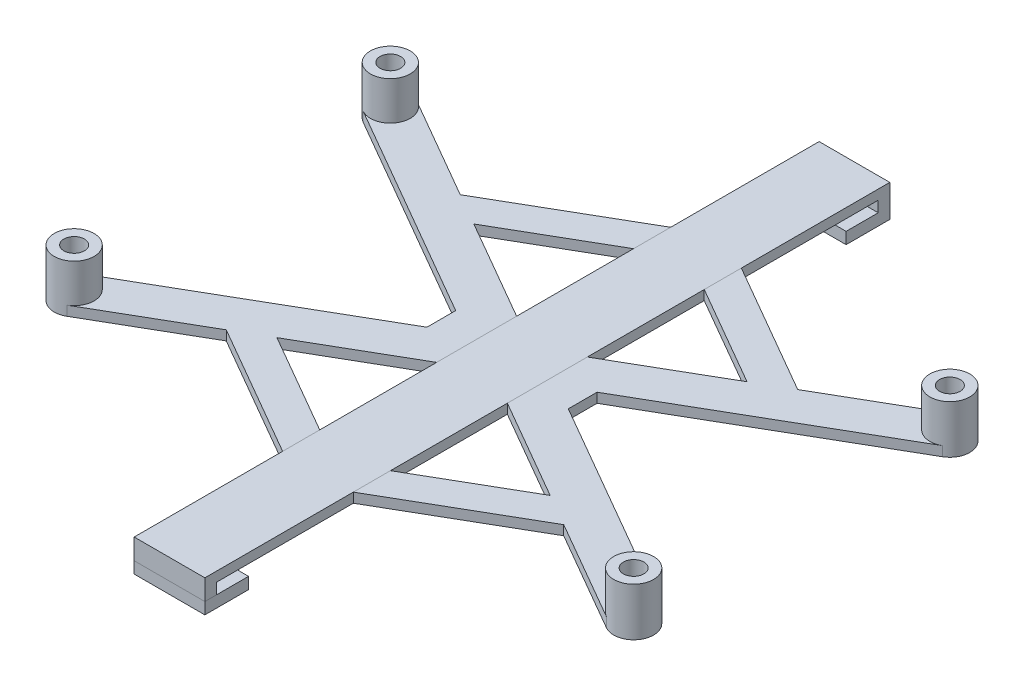
SolidWorks part; units mm, degrees
ref_plane "前视基准面" through (0, 0, 0) normal (0, 0, 1) x (1, 0, 0)
ref_plane "上视基准面" through (0, 0, 0) normal (0, 1, 0) x (1, 0, 0)
ref_plane "右视基准面" through (0, 0, 0) normal (1, 0, 0) x (0, 0, -1)
other "Configuration Table"
sketch "草图1" plane through (0, 0, 0) normal (0, 1, 0) x (1, 0, 0)
  line L0 (-15.0927, 0) -> (15.0927, 0) construction
  line L1 (0, -51.5) -> (0, 51.5) construction
  line L2 (-5.5, 51.5) -> (5.5, 51.5) construction
  line L3 (-5.5, -51.5) -> (5.5, -51.5) construction
  line L4 (-5.5, 51.5) -> (-5.5, 46.5)
  line L5 (-5.5, 46.5) -> (5.5, 46.5)
  line L6 (5.5, 46.5) -> (5.5, 51.5)
  line L7 (-5.5, 51.5) -> (-5.5, 53.3)
  line L8 (-5.5, 53.3) -> (5.5, 53.3)
  line L9 (5.5, 53.3) -> (5.5, 51.5)
  line L10 (-5.5, -51.5) -> (5.5, -51.5) construction
  line L11 (5.5, -53.3) -> (5.5, -51.5)
  line L12 (-5.5, -53.3) -> (5.5, -53.3)
  line L13 (-5.5, -51.5) -> (-5.5, -53.3)
  line L14 (5.5, -46.5) -> (5.5, -51.5)
  line L15 (-5.5, -46.5) -> (5.5, -46.5)
  line L16 (-5.5, -51.5) -> (-5.5, -46.5)
  point P4 (0, 0)
  point P8 (0, 0)
  point P10 (0, 51.5)
  point P21 (0, -51.5)
  dimension "D1" = 11
  dimension "D2" = 103
  dimension "D3" = 5
  dimension "D4" = 1.8
extrude "凸台-拉伸1" add sketch "草图1" against normal blind 1.8 contours L9 L8 L7 L4 L5 L6 | L16 L13 L12 L11 L14 L15
sketch "草图2" plane through (0, 0, 0) normal (0, 1, 0) x (1, 0, 0)
  line L0 (-5.5, 51.5) -> (5.5, 51.5) construction
  line L1 (-5.5, 51.5) -> (5.5, 51.5)
  line L2 (-52.579, 0) -> (52.579, 0) construction
  line L3 (-5.5, -51.5) -> (5.5, -51.5)
  line L4 (5.5, 46.5) -> (5.5, 53.3)
  line L5 (5.5, 53.3) -> (-5.5, 53.3)
  line L6 (-5.5, 53.3) -> (-5.5, 46.5)
  line L7 (-5.5, 46.5) -> (5.5, 46.5)
  line L8 (5.5, 51.5) -> (5.5, 53.3)
  line L9 (5.5, 53.3) -> (-5.5, 53.3)
  line L10 (-5.5, 53.3) -> (-5.5, 51.5)
  line L12 (-5.5, -53.3) -> (-5.5, -51.5)
  line L13 (5.5, -53.3) -> (-5.5, -53.3)
  line L14 (5.5, -51.5) -> (5.5, -53.3)
  point P9 (0, 0)
  dimension "D1" = 0
extrude "凸台-拉伸2" add sketch "草图2" along normal blind 1.7
sketch "草图3" plane through (0, 1.7, 0) normal (0, 1, 0) x (1, 0, 0)
  line L1 (-5.5, 53.3) -> (5.5, 53.3)
  line L2 (-5.5, 53.3) -> (-5.5, -53.3)
  line L3 (-5.5, -53.3) -> (5.5, -53.3)
  line L4 (5.5, 53.3) -> (5.5, -53.3)
extrude "凸台-拉伸3" add sketch "草图3" along normal blind 1.5
sketch "草图4" plane through (0, 3.2, 0) normal (0, 1, 0) x (1, 0, 0)
  line L0 (-100.345, 0) -> (100.345, 0) construction
  line L1 (0, -56.8016) -> (0, 56.8016) construction
  line L2 (-45.09, 21.9203) -> (-11, 2.2385)
  line L3 (-5.5, 53.3) -> (-5.5, -53.3) construction
  line L4 (-41.99, 27.2897) -> (-26.2617, 18.2089)
  line L5 (-5.5, 6.2222) -> (-5.5, -0.937)
  line L6 (41.99, 27.2897) -> (26.2617, 18.2089)
  line L7 (45.09, 21.9203) -> (11, 2.2385)
  line L8 (-5.5, -6.2222) -> (-5.5, 0.937)
  line L9 (45.09, -21.9203) -> (11, -2.2385)
  line L10 (41.99, -27.2897) -> (26.2617, -18.2089)
  line L11 (-45.09, -21.9203) -> (-11, -2.2385)
  line L12 (-41.99, -27.2897) -> (-26.2617, -18.2089)
  line L13 (-21.2617, 15.3222) -> (-5.5, 24.4222)
  line L14 (-26.2617, 18.2089) -> (-5.5, 30.1957)
  line L15 (-5.5, 30.1957) -> (-5.5, 24.4222)
  line L16 (5.5, 30.1957) -> (5.5, 24.4222)
  line L17 (-21.2617, 15.3222) -> (-5.5, 6.2222)
  line L18 (21.2617, 15.3222) -> (5.5, 24.4222)
  line L19 (26.2617, 18.2089) -> (5.5, 30.1957)
  line L20 (21.2617, -15.3222) -> (5.5, -24.4222)
  line L21 (5.5, -30.1957) -> (5.5, -24.4222)
  line L22 (26.2617, -18.2089) -> (5.5, -30.1957)
  line L23 (-21.2617, -15.3222) -> (-5.5, -24.4222)
  line L24 (-5.5, -30.1957) -> (-5.5, -24.4222)
  line L25 (-26.2617, -18.2089) -> (-5.5, -30.1957)
  line L26 (21.2617, 15.3222) -> (5.5, 6.2222)
  line L27 (21.2617, -15.3222) -> (5.5, -6.2222)
  line L28 (-21.2617, -15.3222) -> (-5.5, -6.2222)
  line L29 (-11, 2.2385) -> (-11, -2.2385)
  line L30 (11, 2.2385) -> (11, -2.2385)
  circle A0 centre (43.54, 24.605) radius 1.6
  circle A1 centre (43.54, -24.605) radius 1.6
  circle A2 centre (-43.54, 24.605) radius 1.6
  circle A3 centre (-43.54, -24.605) radius 1.6
  arc A4 (-45.09, 21.9203) -> (-41.99, 27.2897) centre (-43.54, 24.605) cw
  circle A5 centre (43.54, 24.605) radius 3.1
  circle A6 centre (-43.54, -24.605) radius 3.1
  circle A7 centre (43.54, -24.605) radius 3.1
  circle A8 centre (-43.54, 24.605) radius 3.1 construction
  point P4 (0, 0)
  point P8 (0, 0)
  dimension "D1" = 3.2
  dimension "D3" = 87.08
  dimension "D2" = 49.21
  dimension "D7" = 60
  dimension "D8" = 60
  dimension "D9" = 5
  dimension "D10" = 18.2
  dimension "D11" = 22
  dimension "D4" = 1.5
  dimension "D5" = 1.5
  dimension "D6" = 1.5
extrude "凸台-拉伸5" add sketch "草图4" against normal blind 1.5 separate body contours A6 L12 L25 L19 L23 L28 L5 L17 L13 L14 L4 A4 L2 L29 L11 A2 | L10 A7 L9 L30 L7 A5 L6 L19 L29 L18 L26 L27 L20 L22 | A5 A0 | A7 A1 | A6 A3
sketch "草图5" plane through (0, 3.2, 0) normal (0, 1, 0) x (1, 0, 0)
  line L0 (0, -56.8016) -> (0, 56.8016) construction
  line L1 (-100.345, 0) -> (100.345, 0) construction
  line L2 (0, -56.8016) -> (0, 56.8016) construction
  line L3 (-100.345, 0) -> (100.345, 0) construction
  circle A0 centre (43.54, 24.605) radius 1.6 construction
  circle A1 centre (43.54, 24.605) radius 3.1 construction
  circle A2 centre (43.54, 24.605) radius 1.6
  circle A3 centre (43.54, 24.605) radius 3.1
  circle A4 centre (43.54, -24.605) radius 1.6
  circle A5 centre (43.54, -24.605) radius 3.1
  circle A6 centre (-43.54, -24.605) radius 1.6
  circle A7 centre (-43.54, -24.605) radius 3.1
  circle A8 centre (-43.54, 24.605) radius 1.6
  circle A9 centre (-43.54, 24.605) radius 3.1
extrude "凸台-拉伸6" add sketch "草图5" along normal blind 6
